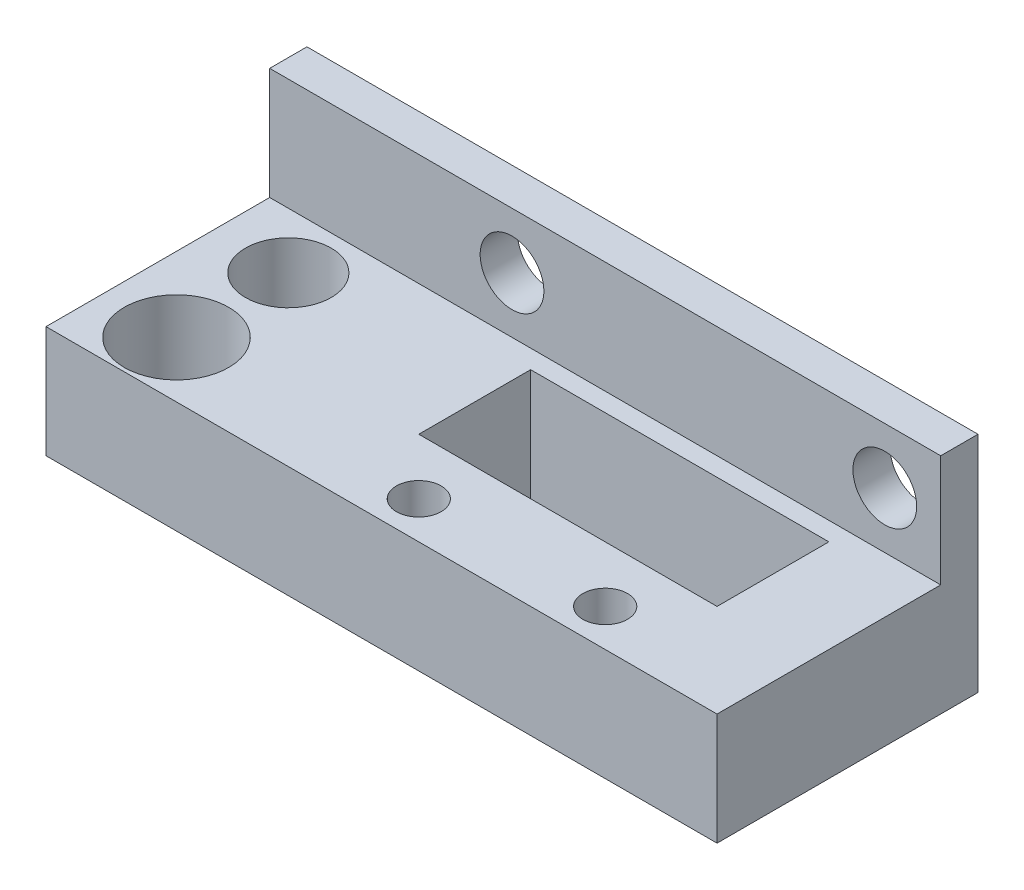
SolidWorks part; units mm, degrees
ref_plane "Front Plane" through (0, 0, 0) normal (0, 0, 1) x (1, 0, 0)
ref_plane "Top Plane" through (0, 0, 0) normal (0, 1, 0) x (1, 0, 0)
ref_plane "Right Plane" through (0, 0, 0) normal (1, 0, 0) x (0, 0, -1)
sketch "Sketch1" plane through (0, 0, 0) normal (0, 1, 0) x (1, 0, 0)
  line L1 (-30.3245, 13.1212) -> (15.3955, 13.1212)
  line L2 (-30.3245, 13.1212) -> (-30.3245, -4.6588)
  line L3 (-30.3245, -4.6588) -> (15.3955, -4.6588)
  line L4 (15.3955, 13.1212) -> (15.3955, -4.6588)
  dimension "D1" = 17.78
  dimension "D2" = 45.72
extrude "Boss-Extrude1" add sketch "Sketch1" along normal blind 7.62
sketch "Sketch2" plane through (0, 7.62, 0) normal (0, 1, 0) x (1, 0, 0)
  line L0 (15.3955, -4.6588) -> (15.3955, 13.1212) construction
  line L1 (-30.3245, 13.1212) -> (15.3955, 13.1212)
  line L2 (-30.3245, 13.1212) -> (-30.3245, 10.5812)
  line L3 (-30.3245, 10.5812) -> (15.3955, 10.5812)
  line L4 (15.3955, 13.1212) -> (15.3955, 10.5812)
  dimension "D1" = 2.54
extrude "Boss-Extrude2" add sketch "Sketch2" along normal blind 7.62
sketch "Sketch3" plane through (0, 0, -13.1212) normal (0, 0, -1) x (-1, 0, 0)
  line L1 (-15.3955, 15.24) -> (30.3245, 15.24) construction
  line L2 (-15.3955, 15.24) -> (-15.3955, 0) construction
  circle A0 centre (13.8145, 11.43) radius 2.1717
  circle A1 centre (-11.5855, 11.43) radius 2.1717
  dimension "D1" = 3.81
  dimension "D3" = 3.81
  dimension "D2" = 3.81
  dimension "D4" = 25.4
extrude "Cut-Extrude1" cut sketch "Sketch3" against normal blind 2.54
sketch "Sketch4" plane through (0, 7.62, 0) normal (0, 1, 0) x (1, 0, 0)
  line L0 (-30.3245, 10.5812) -> (-30.3245, -4.6588) construction
  line L1 (-30.3245, -4.6588) -> (15.3955, -4.6588) construction
  line L2 (15.3955, -4.6588) -> (15.3955, 10.5812) construction
  line L5 (-11.2745, 9.3112) -> (9.0455, 9.3112)
  line L6 (-11.2745, 9.3112) -> (-11.2745, 1.6912)
  line L7 (-11.2745, 1.6912) -> (9.0455, 1.6912)
  line L8 (9.0455, 9.3112) -> (9.0455, 1.6912)
  circle A0 centre (-25.2445, -0.8488) radius 3.556
  circle A1 centre (-25.2445, 6.7712) radius 2.921
  circle A2 centre (-7.4645, -2.1188) radius 1.524
  circle A3 centre (5.2355, -2.1188) radius 1.524
  point P18 (0, 0)
  dimension "D1" = 5.08
  dimension "D3" = 7.112
  dimension "D4" = 5.842
  dimension "D7" = 2.54
  dimension "D8" = 12.7
  dimension "D2" = 3.81
  dimension "D5" = 7.62
  dimension "D6" = 5.08
  dimension "D9" = 10.16
  dimension "D10" = 20.32
  dimension "D11" = 6.35
  dimension "D12" = 7.62
  dimension "D13" = 3.81
  dimension "D14" = 2.54
extrude "Cut-Extrude2" cut sketch "Sketch4" against normal blind 7.62
